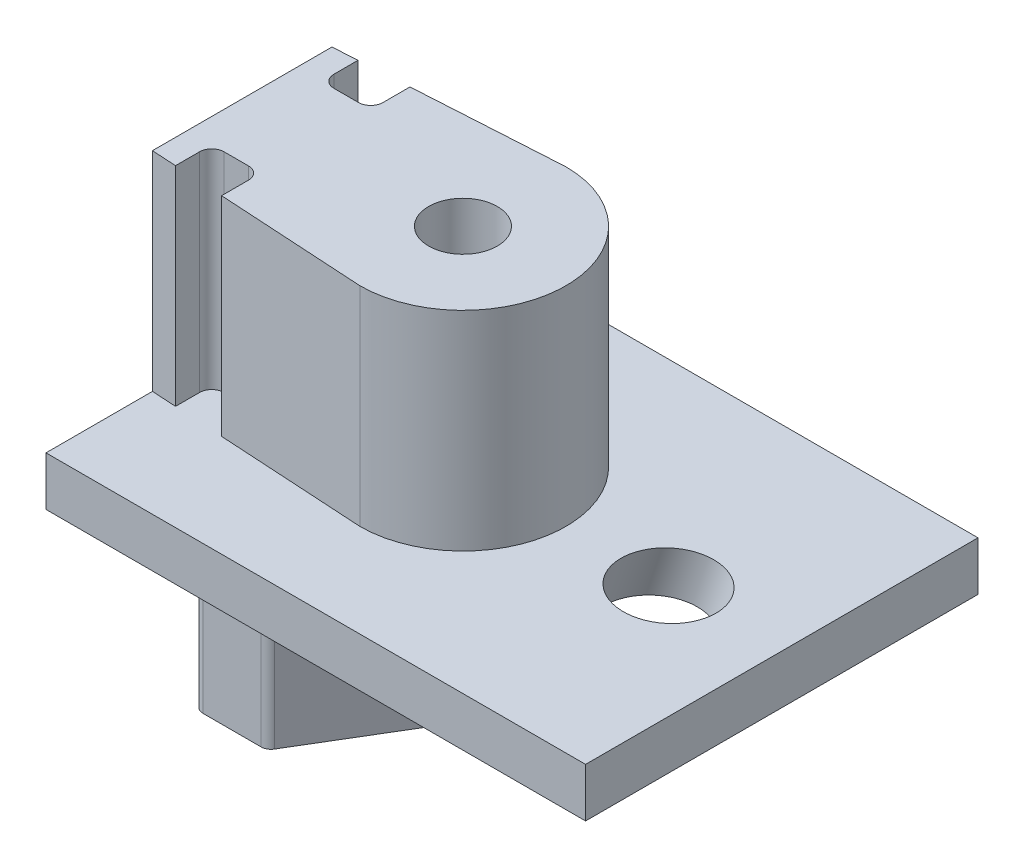
SolidWorks part; units mm, degrees
ref_plane "Front Plane" through (0, 0, 0) normal (0, 0, 1) x (1, 0, 0)
ref_plane "Top Plane" through (0, 0, 0) normal (0, 1, 0) x (1, 0, 0)
ref_plane "Right Plane" through (0, 0, 0) normal (1, 0, 0) x (0, 0, -1)
sketch "Sketch3" plane through (0, 0, 0) normal (0, 1, 0) x (1, 0, 0)
  line L0 (-5, 0.75) -> (0, 1.05) construction
  line L3 (0, -1.05) -> (-5, -0.75) construction
  line L4 (-2.5, 0.9) -> (-2, 0.93)
  line L6 (-4.25, 0) -> (-5.75, 0) construction
  line L7 (-2, 0.93) -> (-2, 0.56)
  line L8 (-2.5, 0.9) -> (-5, 0.9) construction
  line L9 (-2.5, 0.9) -> (-2.5, -0.9)
  line L10 (-2.5, -0.9) -> (-5, -0.9) construction
  line L11 (-5, 0.9) -> (-5, -0.9) construction
  line L12 (-2, 0.96) -> (-1.5, 0.96) construction
  line L13 (-2, 0.96) -> (-2, 0.56) construction
  line L14 (-2, 0.56) -> (-1.5, 0.56)
  line L15 (-1.5, 0.96) -> (-1.5, 0.56)
  line L16 (-1.5, -0.56) -> (-2, -0.56)
  line L17 (-1.5, -0.56) -> (-1.5, -0.96)
  line L18 (-1.5, -0.96) -> (-2, -0.96) construction
  line L19 (-2, -0.56) -> (-2, -0.96) construction
  line L21 (-2.5, -0.9) -> (-2, -0.93)
  line L22 (-2, -0.93) -> (-2, -0.56)
  line L23 (-1.5, 0.96) -> (0, 1.05)
  line L24 (0, -1.05) -> (-1.5, -0.96)
  circle A2 centre (0, 0) radius 0.6 construction
  circle A3 centre (0, 0) radius 0.4 construction
  circle A4 centre (-5, 0) radius 0.35 construction
  circle A5 centre (0, 0) radius 1.05 construction
  circle A6 centre (-5, 0) radius 0.75 construction
  arc A7 (-5, 0.9) -> (-5, -0.9) centre (-5, 0) ccw construction
  arc A8 (0, 1.05) -> (0, -1.05) centre (0, 0) cw
  point P4 (-2, -0.93)
  point P15 (-5, 0)
  point P16 (-2, 0.93)
  point P22 (-5, 0)
  dimension "D2" = 1.2
  dimension "D3" = 0.8
  dimension "D4" = 0.7
  dimension "D6" = 5
  dimension "D1" = 1.5
  dimension "D5" = 2.1
  dimension "D7" = 0.4
  dimension "D9" = 2.5
  dimension "D10" = 1.8
  dimension "D11" = 2.5
  dimension "D12" = 0.5
  dimension "D14" = 1.5
extrude "Boss-Extrude1" add sketch "Sketch3" along normal blind 2.125 contours L21 L22 L16 L17 L24 A8 L23 L15 L14 L7 L4 L9
sketch "Sketch4" plane through (0, 2.125, 0) normal (0, 1, 0) x (1, 0, 0)
  circle A0 centre (0, 0) radius 0.35
  point P9 (0, 0)
  dimension "D1" = 0.7
extrude "Through Holes" cut sketch "Sketch4" against normal through all contours A0
fillet "Fillet1" radius 0.125 4 edges at (-2, 1.0625, 0.56) (-1.5, 1.0625, 0.56) (-1.5, 1.0625, -0.56) (-2, 1.0625, -0.56)
sketch "Sketch5" plane through (0, 0, 0) normal (0, 1, 0) x (1, 0, 0)
  line L0 (-2.25, 0) -> (1.75, 0) construction
  line L1 (-2.25, -2) -> (1.75, -2)
  line L2 (-2.25, -2) -> (-2.25, 2)
  line L3 (-2.25, 2) -> (1.75, 2)
  line L4 (1.75, -2) -> (1.75, 2) construction
  line L5 (-2.25, -2) -> (1.75, 2) construction
  line L6 (-2.25, 2) -> (1.75, -2) construction
  line L8 (1.75, 2) -> (3.25, 2)
  line L9 (3.25, 2) -> (3.25, -2)
  line L10 (3.25, -2) -> (1.75, -2)
  circle A1 centre (0, 0) radius 0.125
  point P1 (-0.25, 0)
  dimension "D2" = 0.25
  dimension "D1" = 1.75
  dimension "D3" = 4
  dimension "D4" = 1.5
  dimension "D5" = 4
extrude "Boss-Extrude2" add sketch "Sketch5" against normal blind 0.5
sketch "Sketch6" plane through (0, 0, 0) normal (0, 0, 1) x (1, 0, 0)
  line L0 (3.25, 0) -> (3.25, 1.25)
  line L1 (3.25, 1.25) -> (1.75, 1.75)
  line L2 (1.75, 1.75) -> (1.75, 0)
  line L3 (1.75, 0) -> (3.25, 0)
  line L4 (2.5, 1.5) -> (1.6412, -1.0764)
  dimension "D1" = 1.25
  dimension "D2" = 1.75
ref_plane "Plane1" through (0.7, 2.1, 0) normal (0.3162, 0.9487, 0) x (0.9487, -0.3162, 0)
sketch "Sketch8" plane through (0.7, 2.1, 0) normal (0.3162, 0.9487, 0) x (0.9487, -0.3162, 0)
  line L0 (2.6879, 0) -> (1.1068, 0) construction
  line L2 (2.6879, 0) -> (1.9879, 0) construction
  circle A0 centre (1.9879, 0) radius 0.46
  dimension "D1" = 0.92
  dimension "D2" = 0.7
extrude "Cut-Extrude1" cut sketch "Sketch8" against normal through all
sketch "Sketch9" plane through (0, 0, 0) normal (0, -1, 0) x (1, 0, 0)
  line L0 (-2.25, 2) -> (-2.25, -2)
  line L1 (-2.25, -2) -> (-3.715, -2)
  line L2 (-3.715, -2) -> (-3.715, 2)
  line L3 (-3.715, 2) -> (-2.25, 2)
extrude "Cut-Extrude2" cut sketch "Sketch9" against normal through all both and the other way through all
sketch "Sketch10" plane through (0, -0.5, 0) normal (0, -1, 0) x (1, 0, 0)
  line L0 (-1.5, 1.25) -> (-1.5, -1.25)
  line L1 (-1.5, -1.25) -> (-0.75, -1.25)
  line L2 (-0.75, -1.25) -> (0, 0)
  line L3 (-2.25, 0) -> (1.75, 0) construction
  line L4 (0, 0) -> (-0.75, 1.25)
  line L5 (-0.75, 1.25) -> (-1.5, 1.25)
  line L6 (0, 0) -> (-1.5, 0) construction
  point P8 (-1.5, 0)
  dimension "D1" = 1.5
  dimension "D2" = 2.5
  dimension "D3" = 0.75
  dimension "D4" = 0.75
extrude "Boss-Extrude3" add sketch "Sketch10" along normal blind 1.75
fillet "Fillet2" radius 0.1 5 edges at (-0.75, -1.375, -1.25) (-0.75, -1.375, 1.25) (-1.5, -1.375, 1.25) (-1.5, -1.375, -1.25) (0, -1.375, 0)
